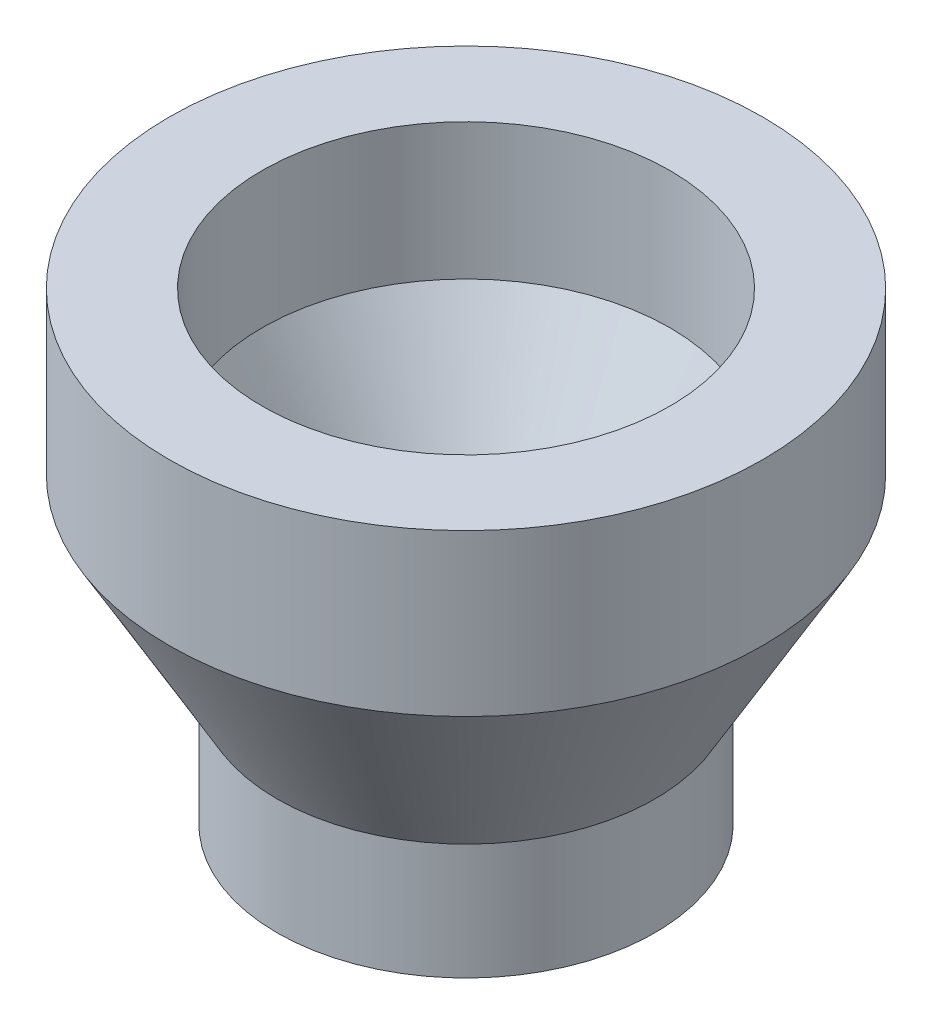
SolidWorks part; units mm, degrees
ref_plane "前视基准面" through (0, 0, 0) normal (0, 0, 1) x (1, 0, 0)
ref_plane "上视基准面" through (0, 0, 0) normal (0, 1, 0) x (1, 0, 0)
ref_plane "右视基准面" through (0, 0, 0) normal (1, 0, 0) x (0, 0, -1)
sketch "草图1" plane through (0, 0, 0) normal (0, 0, 1) x (1, 0, 0)
  line L0 (0, 0) -> (0, 76.5666) construction
  line L1 (-4.075, 22) -> (-4.075, 24.5)
  line L2 (-4.075, 24.5) -> (-6.4, 28.527)
  line L3 (-6.4, 28.527) -> (-6.4, 32)
  line L4 (8, 32) -> (-8, 32) construction
  line L5 (-6.4, 32) -> (-4.4, 32)
  line L6 (-4.8, 32) -> (4.8, 32) construction
  line L7 (-6.3333, 32) -> (6.3333, 32) construction
  line L8 (-4.4, 32) -> (-4.4, 29.0629)
  line L9 (-4.4, 29.0629) -> (-2.575, 25.9019)
  line L10 (-2.575, 25.9019) -> (-2.575, 22)
  line L11 (-2.575, 22) -> (-4.075, 22)
  line L12 (2.7, 22) -> (-2.7, 22) construction
  dimension "D1" = 5.15
  dimension "D2" = 1.5
  dimension "D3" = 2
  dimension "D4" = 12.8
  dimension "D5" = 2
  dimension "D6" = 2.5
  dimension "D7" = 30
revolve "旋转1" add sketch "草图1" angle 360 about L0
